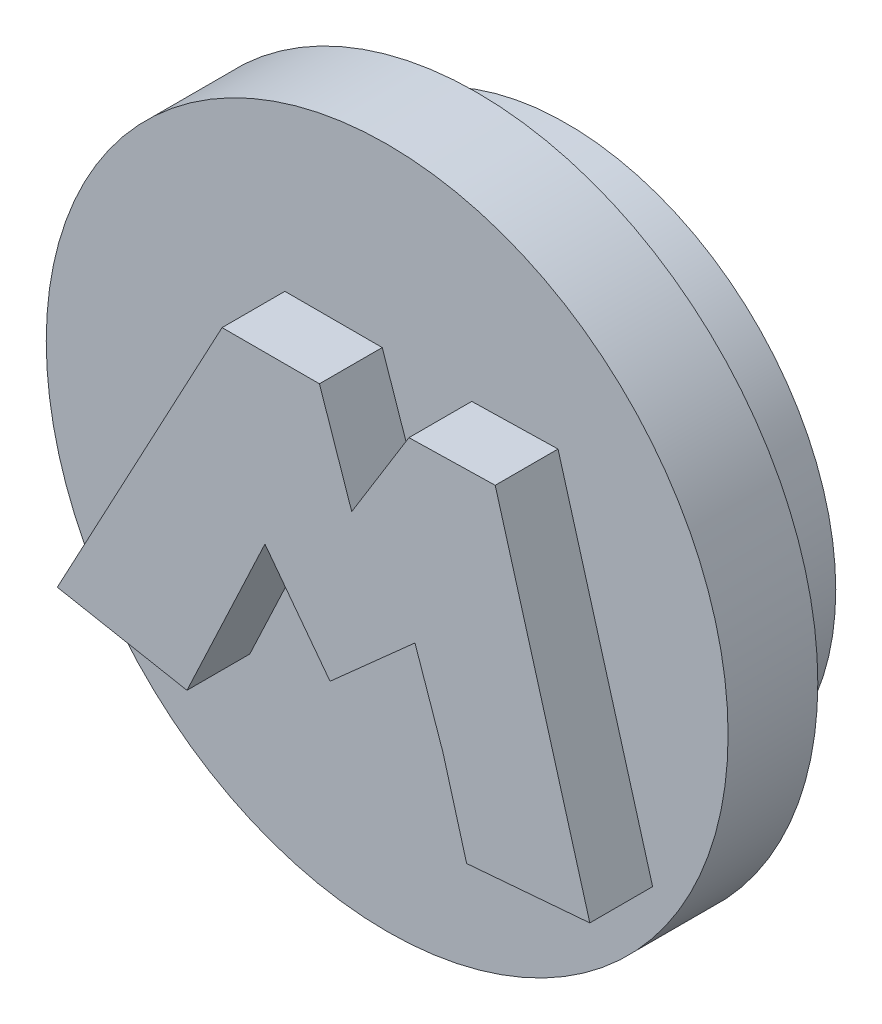
SolidWorks part; units mm, degrees
ref_plane "Plano frontal" through (0, 0, 0) normal (0, 0, 1) x (1, 0, 0)
ref_plane "Plano superior" through (0, 0, 0) normal (0, 1, 0) x (1, 0, 0)
ref_plane "Plano direito" through (0, 0, 0) normal (1, 0, 0) x (0, 0, -1)
sketch "Esboço1" plane through (0, 0, 0) normal (0, 0, 1) x (1, 0, 0)
  circle A0 centre (0, 0) radius 19
  point P3 (0, 0)
  point P4 (0, 0)
  point P6 (0, 0)
  dimension "D1" = 38
extrude "Ressalto-extrusão1" add sketch "Esboço1" along normal mid plane 5
sketch "Esboço2" plane through (0, 0, -2.5) normal (0, 0, -1) x (-1, 0, 0)
  circle A0 centre (0, 0) radius 15
  dimension "D1" = 30
extrude "Ressalto-extrusão2" add sketch "Esboço2" along normal blind 5
sketch "Esboço4" plane through (0, 0, 2.5) normal (0, 0, 1) x (1, 0, 0)
  line L0 (-19, 0) -> (19, 0) construction
  line L1 (0, -10) -> (0, 10) construction
  line L2 (-16.1555, 10) -> (16.1555, 10) construction
  line L3 (-16.1555, -10) -> (16.1555, -10) construction
  circle A0 centre (0, 0) radius 19 construction
  text T0 "M" font "Super Mario 256" height in points 72
  point P7 (0, 0)
  point P11 (0, 0)
  point P14 (0, 10)
  point P16 (0, -10)
extrude "Ressalto-extrusão3" add sketch "Esboço4" along normal blind 3.5
